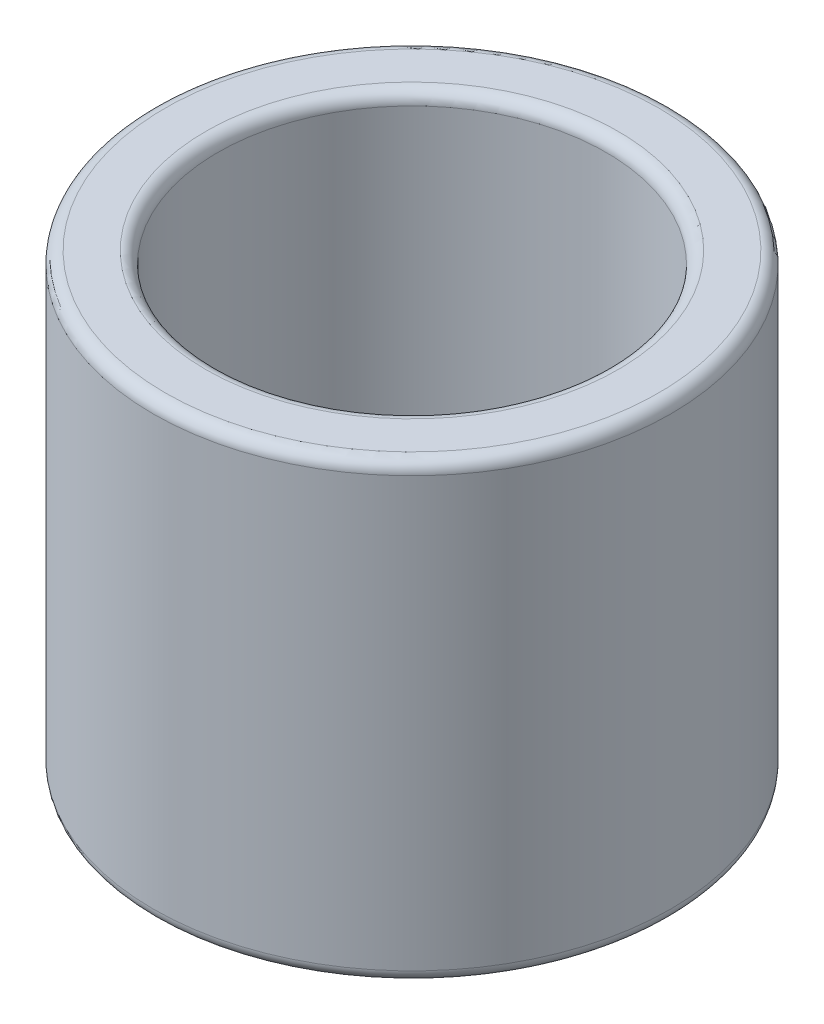
SolidWorks part; units mm, degrees
ref_plane "前视基准面" through (0, 0, 0) normal (0, 0, 1) x (1, 0, 0)
ref_plane "上视基准面" through (0, 0, 0) normal (0, 1, 0) x (1, 0, 0)
ref_plane "右视基准面" through (0, 0, 0) normal (1, 0, 0) x (0, 0, -1)
sketch "草图1" plane through (0, 0, 0) normal (0, 1, 0) x (1, 0, 0)
  circle A0 centre (0, 0) radius 12
  circle A1 centre (0, 0) radius 16
  dimension "D1" = 32
  dimension "D2" = 24
extrude "凸台-拉伸1" add sketch "草图1" along normal mid plane 28
fillet "圆角1" radius 0.75 4 edges at (0, -14, 12) (0, -14, 16) (0, 14, 12) (0, 14, 16)
